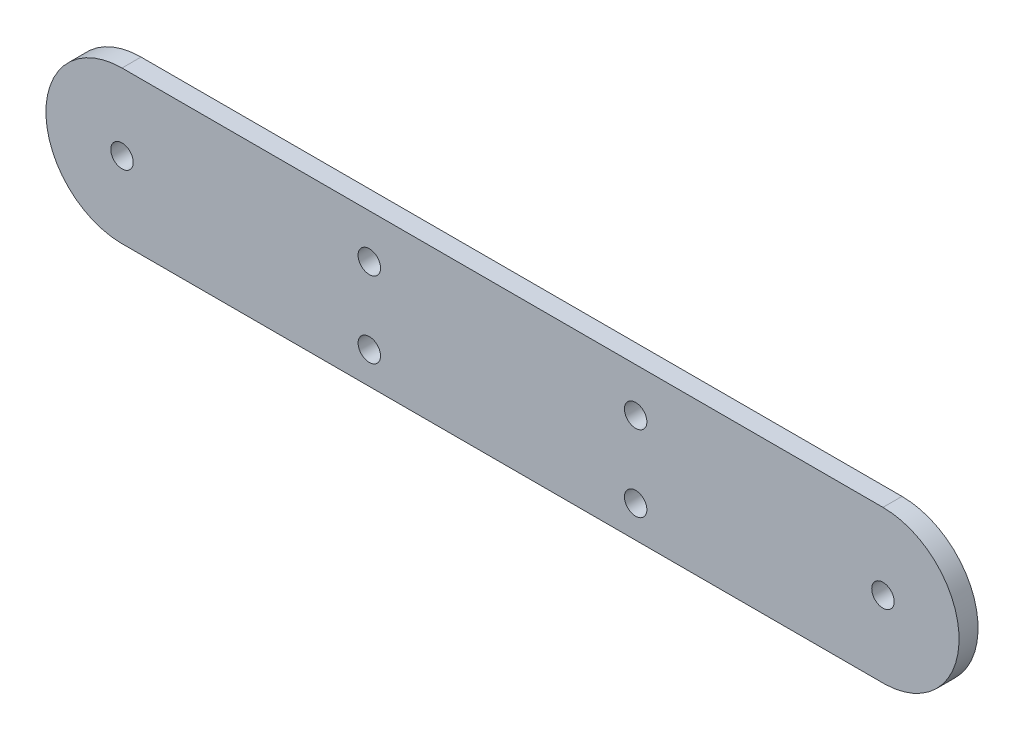
SolidWorks part; units mm, degrees
ref_plane "Alzado" through (0, 0, 0) normal (0, 0, 1) x (1, 0, 0)
ref_plane "Planta" through (0, 0, 0) normal (0, 1, 0) x (1, 0, 0)
ref_plane "Vista lateral" through (0, 0, 0) normal (1, 0, 0) x (0, 0, -1)
sketch "Croquis2" plane through (0, 0, 0) normal (0, 0, 1) x (1, 0, 0)
  line L0 (0, 0) -> (0, 61.9329) construction
  line L1 (0, 0) -> (193.1851, 3.0365) construction
  line L2 (100.6286, -18.4183) -> (-100.6286, -18.4183)
  line L4 (100, 21.5718) -> (-100, 21.5718)
  arc A0 (100.6286, -18.4183) -> (100, 21.5718) centre (99.9999, 1.5718) ccw
  arc A1 (-100.6286, -18.4183) -> (-100, 21.5718) centre (-99.9999, 1.5718) cw
  dimension "D1" = 20
  dimension "D2" = 200
extrude "Extruir1" add sketch "Croquis2" along normal mid plane 5
sketch "Croquis3" plane through (0, 0, 2.5) normal (0, 0, 1) x (1, 0, 0)
  line L0 (0, 0) -> (0, 57.739) construction
  circle A1 centre (99.9999, 1.5718) radius 2.95
  circle A2 centre (-99.9999, 1.5718) radius 2.95
  dimension "D1" = 5.9
extrude "Cortar-Extruir1" cut sketch "Croquis3" against normal blind 10
sketch "Croquis4" plane through (0, 0, 2.5) normal (0, 0, 1) x (1, 0, 0)
  circle A0 centre (-35, 10) radius 2.95
  circle A1 centre (-35, -10) radius 2.95
  circle A2 centre (35, -10) radius 2.95
  circle A3 centre (35, 10) radius 2.95
extrude "Cortar-Extruir2" cut sketch "Croquis4" against normal blind 10
